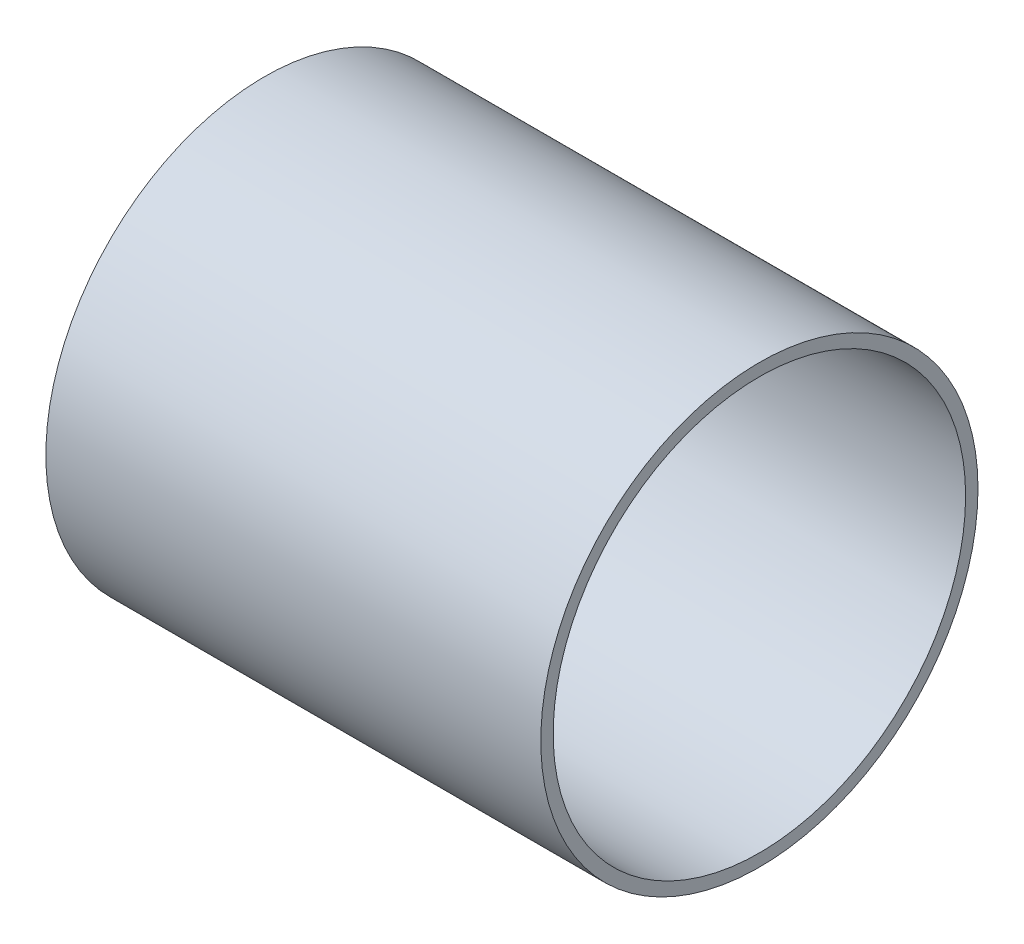
SolidWorks part; units mm, degrees
material "Сталь 3 ГОСТ 380-2005"
ref_plane "Спереди" through (0, 0, 0) normal (0, 0, 1) x (1, 0, 0)
ref_plane "Сверху" through (0, 0, 0) normal (0, 1, 0) x (1, 0, 0)
ref_plane "Справа" through (0, 0, 0) normal (1, 0, 0) x (0, 0, -1)
sketch "Эскиз1" plane through (0, 0, 0) normal (0, 0, 1) x (1, 0, 0)
  line L0 (0, 0) -> (-65.8356, 0) construction
  line L2 (0, 75) -> (180, 75)
  line L3 (0, 75) -> (0, 79.5)
  line L4 (0, 79.5) -> (180, 79.5)
  line L5 (180, 75) -> (180, 79.5)
  dimension "D1" = 159
  dimension "D2" = 150
  dimension "D3" = 180
revolve "Повернуть1" add sketch "Эскиз1" angle 360 about L0
